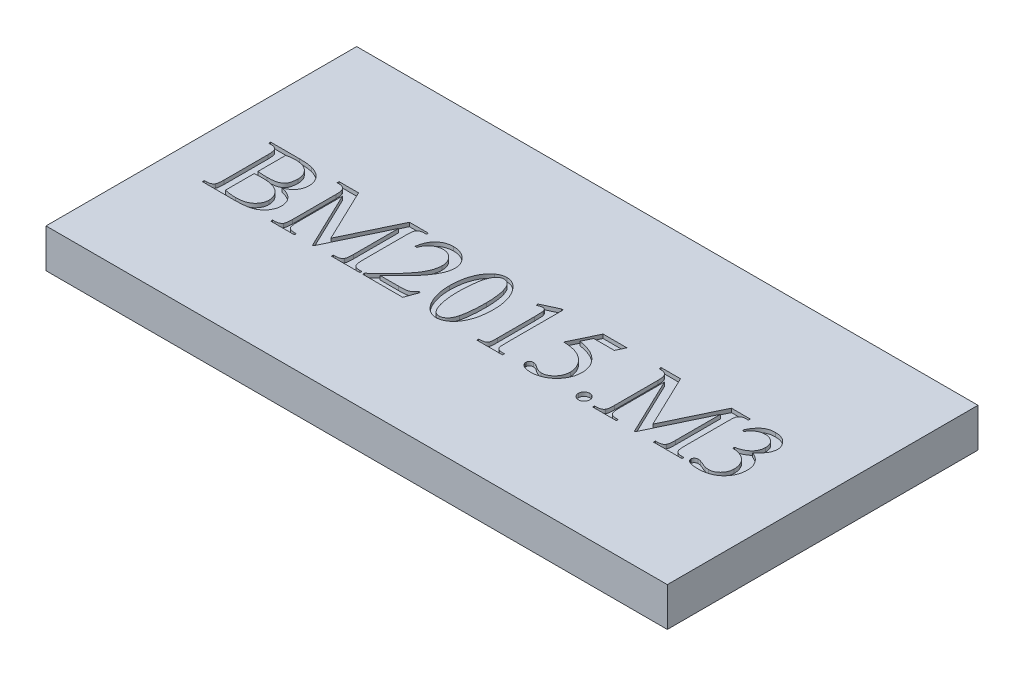
SolidWorks part; units mm, degrees
material "Д16Т ГОСТ 4784-74"
ref_plane "Спереди" through (0, 0, 0) normal (0, 0, 1) x (1, 0, 0)
ref_plane "Сверху" through (0, 0, 0) normal (0, 1, 0) x (1, 0, 0)
ref_plane "Сбоку" through (0, 0, 0) normal (1, 0, 0) x (0, 0, -1)
sketch "Эскиз1" plane through (0, 0, 0) normal (0, 1, 0) x (1, 0, 0)
  line L1 (-80, -40) -> (80, -40)
  line L2 (-80, -40) -> (-80, 40)
  line L3 (-80, 40) -> (80, 40)
  line L4 (80, -40) -> (80, 40)
  line L5 (-80, -40) -> (80, 40) construction
  line L6 (-80, 40) -> (80, -40) construction
  point P0 (0, 0)
  dimension "D1" = 80
  dimension "D2" = 160
extrude "Бобышка-Вытянуть1" add sketch "Эскиз1" along normal blind 10
sketch "Эскиз2" plane through (0, 10, 0) normal (0, 1, 0) x (1, 0, 0)
  line L0 (80, 40) -> (-80, 40) construction
  line L1 (-80, 40) -> (-80, -40) construction
  text T0 "BM2015.M3" font "Times New Roman" height in points 72
  dimension "D1" = 50
  dimension "D2" = 10
extrude "Вырез-Вытянуть1" cut sketch "Эскиз2" against normal blind 1
